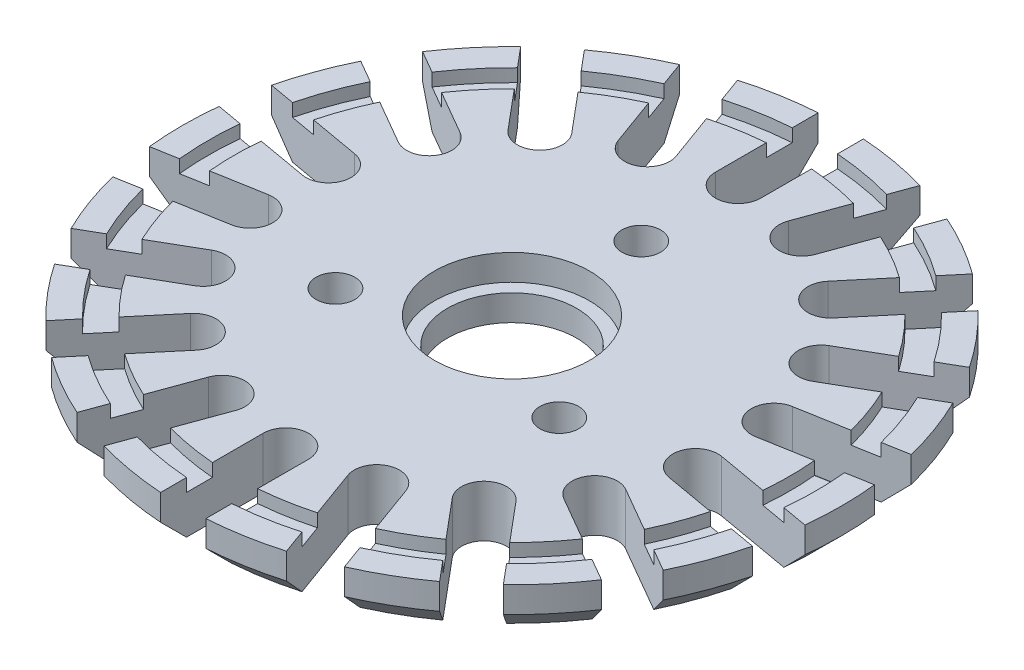
SolidWorks part; units mm, degrees
material "Liga 1060"
ref_plane "Plano frontal" through (0, 0, 0) normal (0, 0, 1) x (1, 0, 0)
ref_plane "Plano superior" through (0, 0, 0) normal (0, 1, 0) x (1, 0, 0)
ref_plane "Plano direito" through (0, 0, 0) normal (1, 0, 0) x (0, 0, -1)
sketch "Esboço1" plane through (0, 0, 0) normal (0, 1, 0) x (1, 0, 0)
  line L0 (1.75, 17.5) -> (1.75, 25.4399)
  line L1 (-1.75, 17.5) -> (-1.75, 25.4399)
  line L2 (4.3409, 17.0432) -> (7.0565, 24.5042)
  line L3 (7.6298, 15.8461) -> (10.3454, 23.3071)
  line L4 (9.9082, 14.5307) -> (15.0119, 20.613)
  line L5 (12.5894, 12.2809) -> (17.693, 18.3632)
  line L6 (14.2804, 10.2655) -> (21.1566, 14.2355)
  line L7 (16.0304, 7.2345) -> (22.9066, 11.2044)
  line L8 (16.9303, 4.7623) -> (24.7495, 6.141)
  line L9 (17.538, 1.3154) -> (25.3573, 2.6942)
  line L10 (17.538, -1.3154) -> (25.3573, -2.6942)
  line L11 (16.9303, -4.7623) -> (24.7495, -6.141)
  line L12 (16.0304, -7.2345) -> (22.9066, -11.2044)
  line L13 (14.2804, -10.2655) -> (21.1566, -14.2355)
  line L14 (12.5894, -12.2809) -> (17.693, -18.3632)
  line L15 (9.9082, -14.5307) -> (15.0119, -20.613)
  line L16 (7.6298, -15.8461) -> (10.3454, -23.3071)
  line L17 (4.3409, -17.0432) -> (7.0565, -24.5042)
  line L18 (1.75, -17.5) -> (1.75, -25.4399)
  line L19 (-1.75, -17.5) -> (-1.75, -25.4399)
  line L20 (-4.3409, -17.0432) -> (-7.0565, -24.5042)
  line L21 (-7.6298, -15.8461) -> (-10.3454, -23.3071)
  line L22 (-9.9082, -14.5307) -> (-15.0119, -20.613)
  line L23 (-12.5894, -12.2809) -> (-17.693, -18.3632)
  line L24 (-14.2804, -10.2655) -> (-21.1566, -14.2355)
  line L25 (-16.0304, -7.2345) -> (-22.9066, -11.2044)
  line L26 (-16.9303, -4.7623) -> (-24.7495, -6.141)
  line L27 (-17.538, -1.3154) -> (-25.3573, -2.6942)
  line L28 (-17.538, 1.3154) -> (-25.3573, 2.6942)
  line L29 (-16.9303, 4.7623) -> (-24.7495, 6.141)
  line L30 (-16.0304, 7.2345) -> (-22.9066, 11.2044)
  line L31 (-14.2804, 10.2655) -> (-21.1566, 14.2355)
  line L32 (-12.5894, 12.2809) -> (-17.693, 18.3632)
  line L33 (-9.9082, 14.5307) -> (-15.0119, 20.613)
  line L34 (-7.6298, 15.8461) -> (-10.3454, 23.3071)
  line L35 (-4.3409, 17.0432) -> (-7.0565, 24.5042)
  arc A0 (-1.75, 25.4399) -> (-7.0565, 24.5042) centre (0, 0) ccw
  circle A1 centre (0, 0) radius 5
  circle A2 centre (0, 0) radius 17.5 construction
  arc A3 (-1.75, 17.5) -> (1.75, 17.5) centre (0, 17.5) ccw
  arc A4 (4.3409, 17.0432) -> (7.6298, 15.8461) centre (5.9854, 16.4446) ccw
  arc A5 (9.9082, 14.5307) -> (12.5894, 12.2809) centre (11.2488, 13.4058) ccw
  arc A6 (14.2804, 10.2655) -> (16.0304, 7.2345) centre (15.1554, 8.75) ccw
  arc A7 (16.9303, 4.7623) -> (17.538, 1.3154) centre (17.2341, 3.0388) ccw
  arc A8 (17.538, -1.3154) -> (16.9303, -4.7623) centre (17.2341, -3.0388) ccw
  arc A9 (16.0304, -7.2345) -> (14.2804, -10.2655) centre (15.1554, -8.75) ccw
  arc A10 (12.5894, -12.2809) -> (9.9082, -14.5307) centre (11.2488, -13.4058) ccw
  arc A11 (7.6298, -15.8461) -> (4.3409, -17.0432) centre (5.9854, -16.4446) ccw
  arc A12 (1.75, -17.5) -> (-1.75, -17.5) centre (0, -17.5) ccw
  arc A13 (-4.3409, -17.0432) -> (-7.6298, -15.8461) centre (-5.9854, -16.4446) ccw
  arc A14 (-9.9082, -14.5307) -> (-12.5894, -12.2809) centre (-11.2488, -13.4058) ccw
  arc A15 (-14.2804, -10.2655) -> (-16.0304, -7.2345) centre (-15.1554, -8.75) ccw
  arc A16 (-16.9303, -4.7623) -> (-17.538, -1.3154) centre (-17.2341, -3.0388) ccw
  arc A17 (-17.538, 1.3154) -> (-16.9303, 4.7623) centre (-17.2341, 3.0388) ccw
  arc A18 (-16.0304, 7.2345) -> (-14.2804, 10.2655) centre (-15.1554, 8.75) ccw
  arc A19 (-12.5894, 12.2809) -> (-9.9082, 14.5307) centre (-11.2488, 13.4058) ccw
  arc A20 (-7.6298, 15.8461) -> (-4.3409, 17.0432) centre (-5.9854, 16.4446) ccw
  arc A21 (-10.3454, 23.3071) -> (-15.0119, 20.613) centre (0, 0) ccw
  arc A22 (7.0565, 24.5042) -> (1.75, 25.4399) centre (0, 0) ccw
  arc A23 (-17.693, 18.3632) -> (-21.1566, 14.2355) centre (0, 0) ccw
  arc A24 (-22.9066, 11.2044) -> (-24.7495, 6.141) centre (0, 0) ccw
  arc A25 (-25.3573, 2.6942) -> (-25.3573, -2.6942) centre (0, 0) ccw
  arc A26 (-24.7495, -6.141) -> (-22.9066, -11.2044) centre (0, 0) ccw
  arc A27 (-21.1566, -14.2355) -> (-17.693, -18.3632) centre (0, 0) ccw
  arc A28 (-15.0119, -20.613) -> (-10.3454, -23.3071) centre (0, 0) ccw
  arc A29 (-7.0565, -24.5042) -> (-1.75, -25.4399) centre (0, 0) ccw
  arc A30 (1.75, -25.4399) -> (7.0565, -24.5042) centre (0, 0) ccw
  arc A31 (10.3454, -23.3071) -> (15.0119, -20.613) centre (0, 0) ccw
  arc A32 (17.693, -18.3632) -> (21.1566, -14.2355) centre (0, 0) ccw
  arc A33 (22.9066, -11.2044) -> (24.7495, -6.141) centre (0, 0) ccw
  arc A34 (25.3573, -2.6942) -> (25.3573, 2.6942) centre (0, 0) ccw
  arc A35 (24.7495, 6.141) -> (22.9066, 11.2044) centre (0, 0) ccw
  arc A36 (21.1566, 14.2355) -> (17.693, 18.3632) centre (0, 0) ccw
  arc A37 (15.0119, 20.613) -> (10.3454, 23.3071) centre (0, 0) ccw
  dimension "D1" = 51
  dimension "D2" = 10
  dimension "D3" = 35
  dimension "D4" = 3.5
  dimension "D5" = 7.9399
extrude "Ressalto-extrusão1" add sketch "Esboço1" along normal blind 4
sketch "Esboço2" plane through (0, 4, 0) normal (0, 1, 0) x (1, 0, 0)
  circle A0 centre (0, 0) radius 6
  dimension "D1" = 12
extrude "Corte-extrusão1" cut sketch "Esboço2" against normal blind 2
sketch "Esboço3" plane through (0, 4, 0) normal (0, 1, 0) x (1, 0, 0)
  circle A0 centre (0, 0) radius 23.5
  circle A1 centre (0, 0) radius 21.5
  dimension "D1" = 47
  dimension "D2" = 43
extrude "Corte-extrusão2" cut sketch "Esboço3" against normal blind 1
chamfer "Chanfro1" distance 2 angle 45 18 edges at (25.5, 0, 0) (23.9622, 0, 8.7215) (19.5341, 0, 16.3911) (12.75, 0, 22.0836) (4.428, 0, 25.1126) (-4.428, 0, 25.1126) (-12.75, 0, 22.0836) (-19.5341, 0, 16.3911) (-23.9622, 0, 8.7215) (-25.5, 0, 0) (-23.9622, 0, -8.7215) (-19.5341, 0, -16.3911) (-12.75, 0, -22.0836) (-4.428, 0, -25.1126) (4.428, 0, -25.1126) (12.75, 0, -22.0836) (19.5341, 0, -16.3911) (23.9622, 0, -8.7215)
sketch "Esboço4" plane through (0, 0, 0) normal (0, -1, 0) x (1, 0, 0)
  line L0 (0, -12.8935) -> (0, 12.7623) construction
  circle A0 centre (0, 0) radius 10 construction
  circle A1 centre (0, -10) radius 1.5
  circle A2 centre (-8.6603, 5) radius 1.5
  circle A3 centre (8.6603, 5) radius 1.5
  dimension "D1" = 20
  dimension "D2" = 3
  dimension "D4" = 10
  dimension "D5" = 10
  dimension "D3" = 3
extrude "Corte-extrusão3" cut sketch "Esboço4" against normal through all
